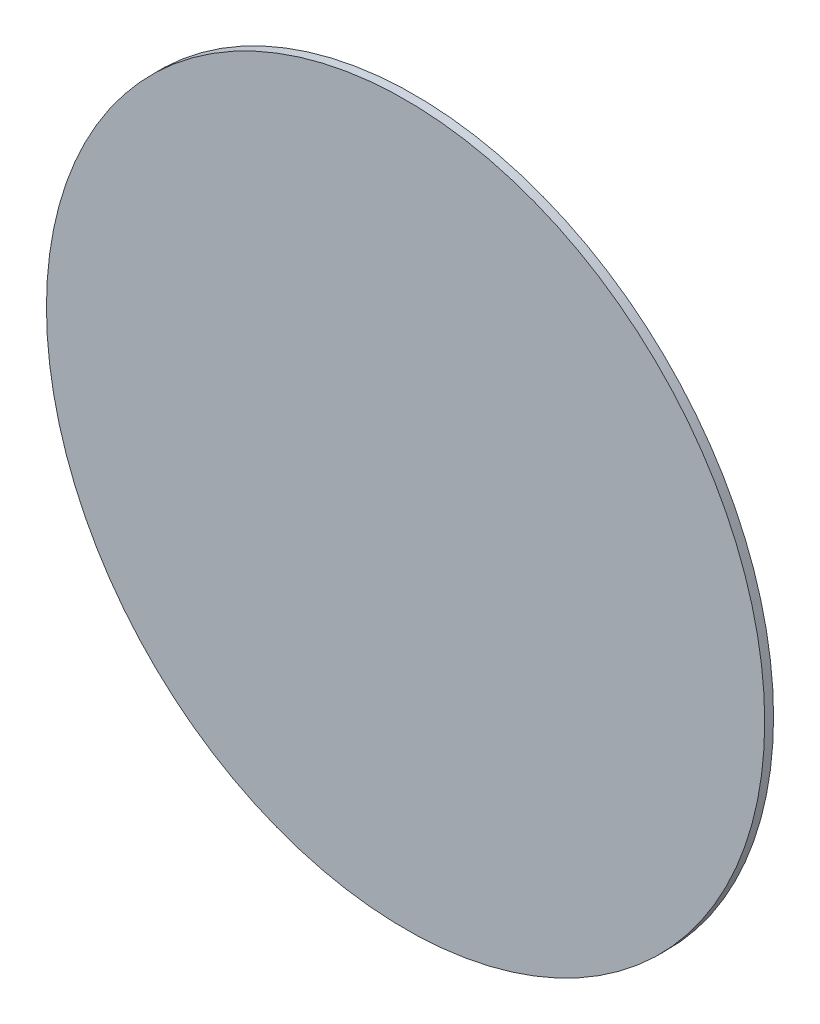
SolidWorks part; units mm, degrees
ref_plane "Front Plane" through (0, 0, 0) normal (0, 0, 1) x (1, 0, 0)
ref_plane "Top Plane" through (0, 0, 0) normal (0, 1, 0) x (1, 0, 0)
ref_plane "Right Plane" through (0, 0, 0) normal (1, 0, 0) x (0, 0, -1)
sketch "Sketch1" plane through (0, 0, 0) normal (0, 0, 1) x (1, 0, 0)
  circle A0 centre (0, 0) radius 65
  dimension "D1" = 130
extrude "Boss-Extrude1" add sketch "Sketch1" along normal blind 1.6
